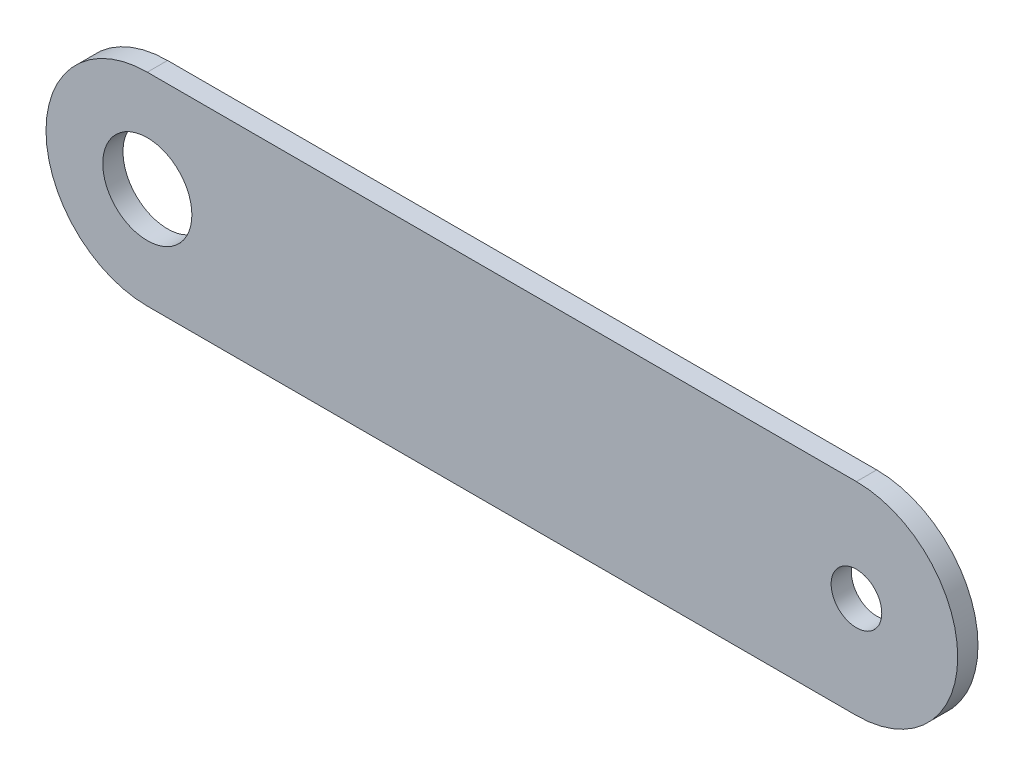
SolidWorks part; units mm, degrees
ref_plane "Front Plane" through (0, 0, 0) normal (0, 0, 1) x (1, 0, 0)
ref_plane "Top Plane" through (0, 0, 0) normal (0, 1, 0) x (1, 0, 0)
ref_plane "Right Plane" through (0, 0, 0) normal (1, 0, 0) x (0, 0, -1)
sketch "Sketch1" plane through (0, 0, 0) normal (0, 0, 1) x (1, 0, 0)
  line L0 (-18.6709, 0) -> (51.3291, 0) construction
  line L1 (-18.6709, 10) -> (51.3291, 10)
  line L2 (-18.6709, -10) -> (51.3291, -10)
  arc A0 (-18.6709, 10) -> (-18.6709, -10) centre (-18.6709, 0) ccw
  arc A1 (51.3291, -10) -> (51.3291, 10) centre (51.3291, 0) ccw
  circle A2 centre (-18.6709, 0) radius 4.4
  circle A4 centre (51.3291, 0) radius 2.5
  point P3 (16.3291, 0)
  point P14 (31.3291, -0.0931)
  dimension "D1" = 20
  dimension "D2" = 70
extrude "Boss-Extrude1" add sketch "Sketch1" along normal blind 2
